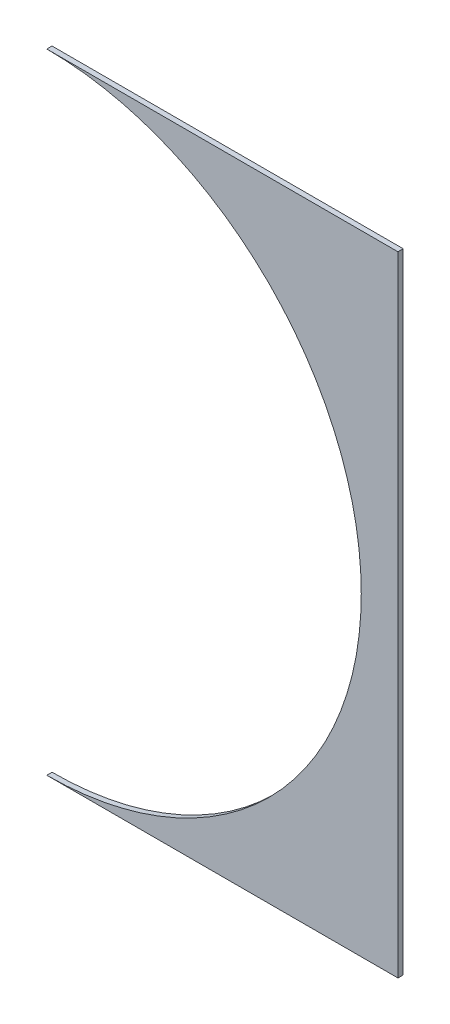
SolidWorks part; units mm, degrees
ref_plane "Front Plane" through (0, 0, 0) normal (0, 0, 1) x (1, 0, 0)
ref_plane "Top Plane" through (0, 0, 0) normal (0, 1, 0) x (1, 0, 0)
ref_plane "Right Plane" through (0, 0, 0) normal (1, 0, 0) x (0, 0, -1)
sketch "Sketch1" plane through (0, 0, 0) normal (0, 0, 1) x (1, 0, 0)
  line L1 (0, 0) -> (212.725, 0)
  line L2 (0, 0) -> (0, 381)
  line L3 (0, 381) -> (212.725, 381)
  line L4 (212.725, 0) -> (212.725, 381)
  arc A0 (0, 0) -> (0, 381) centre (0, 190.5) ccw
  dimension "D1" = 381
  dimension "D2" = 212.725
extrude "Boss-Extrude1" add sketch "Sketch1" along normal blind 3.175 contours A0 L1 L4 L3
